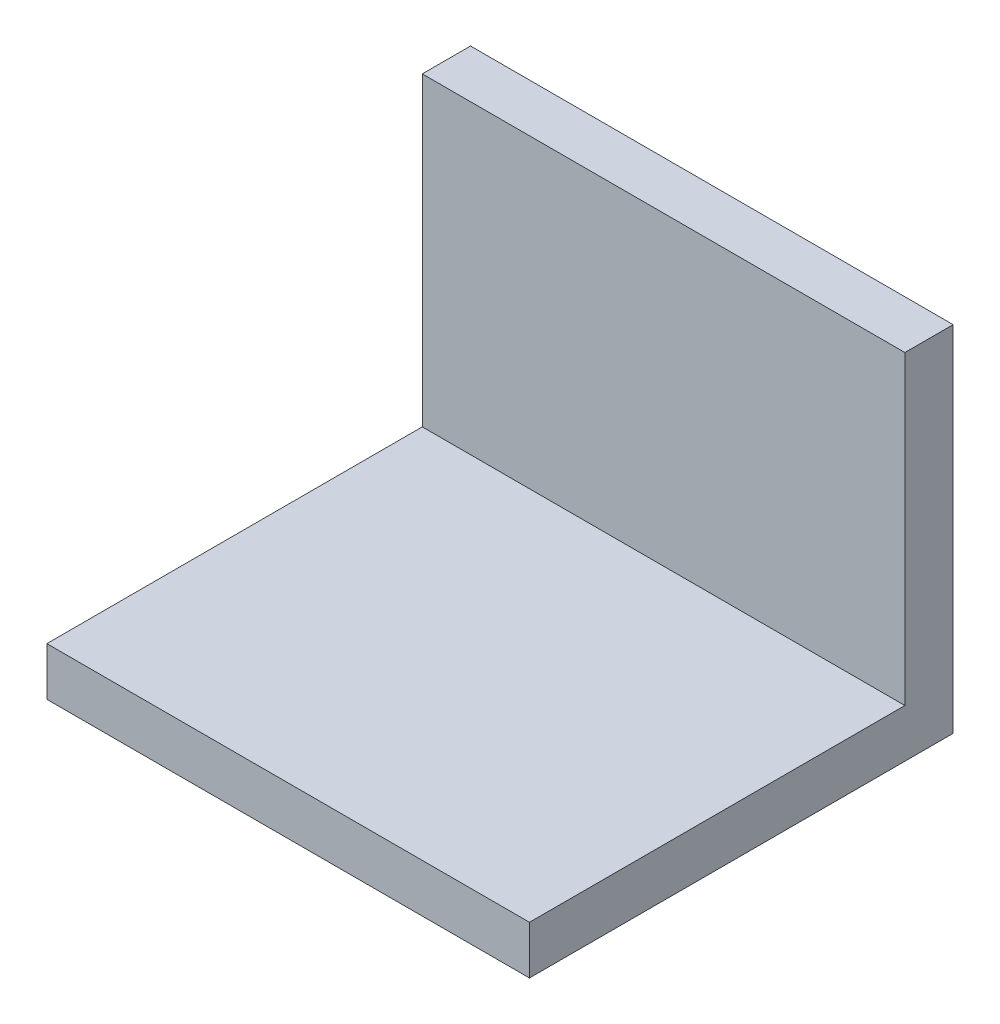
SolidWorks part; units mm, degrees
ref_plane "Front Plane" through (0, 0, 0) normal (0, 0, 1) x (1, 0, 0)
ref_plane "Top Plane" through (0, 0, 0) normal (0, 1, 0) x (1, 0, 0)
ref_plane "Right Plane" through (0, 0, 0) normal (1, 0, 0) x (0, 0, -1)
sketch "Sketch1" plane through (0, 0, 0) normal (1, 0, 0) x (0, 0, -1)
  line L0 (0, 0) -> (66.894, 0)
  line L1 (66.894, 0) -> (66.894, 55.8859)
  line L2 (66.894, 55.8859) -> (59.274, 55.8859)
  line L3 (59.274, 55.8859) -> (59.274, 7.62)
  line L4 (59.274, 7.62) -> (0, 7.62)
  line L5 (0, 7.62) -> (0, 0)
extrude "Extrude1" add sketch "Sketch1" against normal blind 76.2
ref_plane "Plane1" through (0, 4.5819, 3.731) normal (0, 0.7754, 0.6314) x (1, 0, 0)
